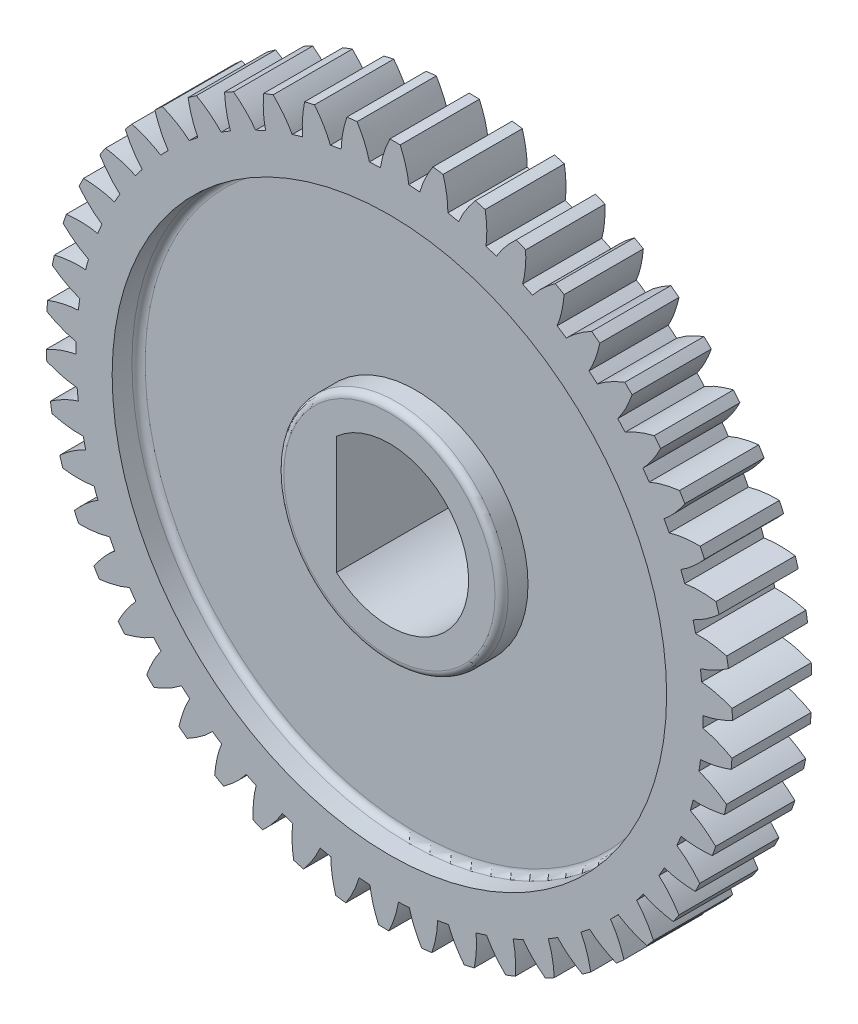
SolidWorks part; units mm, degrees
ref_plane "Plan de face" through (0, 0, 0) normal (0, 0, 1) x (1, 0, 0)
ref_plane "Plan de dessus" through (0, 0, 0) normal (0, 1, 0) x (1, 0, 0)
ref_plane "Plan de droite" through (0, 0, 0) normal (1, 0, 0) x (0, 0, -1)
sketch "Esquisse1" plane through (0, 0, 0) normal (0, 0, 1) x (1, 0, 0)
  line L0 (-2, 2.2361) -> (-2, -2.2361)
  arc A0 (12.9936, 0.4084) -> (12.9756, 0.7954) centre (0, 0) ccw
  arc A1 (12.8399, 2.0337) -> (12.7736, 2.4154) centre (0, 0) ccw
  arc A2 (12.4838, 3.6269) -> (12.3702, 3.9974) centre (0, 0) ccw
  arc A3 (11.9308, 5.1629) -> (11.7716, 5.5162) centre (0, 0) ccw
  arc A4 (11.1896, 6.6175) -> (10.9874, 6.9481) centre (0, 0) ccw
  arc A5 (10.272, 7.9678) -> (10.03, 8.2704) centre (0, 0) ccw
  arc A6 (9.1924, 9.1924) -> (8.9143, 9.4623) centre (0, 0) ccw
  arc A7 (7.9678, 10.272) -> (7.6581, 10.5049) centre (0, 0) ccw
  arc A8 (6.6175, 11.1897) -> (6.2811, 11.3819) centre (0, 0) ccw
  arc A9 (5.1629, 11.9308) -> (4.805, 12.0794) centre (0, 0) ccw
  arc A10 (3.6269, 12.4838) -> (3.2532, 12.5864) centre (0, 0) ccw
  arc A11 (2.0336, 12.84) -> (1.6501, 12.8949) centre (0, 0) ccw
  arc A12 (0.4083, 12.9936) -> (0.0209, 13) centre (0, 0) ccw
  arc A13 (-1.2234, 12.9423) -> (-1.6086, 12.9001) centre (0, 0) ccw
  arc A14 (-2.8359, 12.6869) -> (-3.2127, 12.5968) centre (0, 0) ccw
  arc A15 (-4.4036, 12.2314) -> (-4.7662, 12.0948) centre (0, 0) ccw
  arc A16 (-5.9019, 11.5831) -> (-6.2445, 11.402) centre (0, 0) ccw
  arc A17 (-7.3071, 10.752) -> (-7.6243, 10.5295) centre (0, 0) ccw
  arc A18 (-8.5971, 9.7514) -> (-8.8839, 9.4909) centre (0, 0) ccw
  arc A19 (-9.7515, 8.597) -> (-10.0033, 8.3026) centre (0, 0) ccw
  arc A20 (-10.7521, 7.3071) -> (-10.9651, 6.9834) centre (0, 0) ccw
  arc A21 (-11.5831, 5.9019) -> (-11.7538, 5.554) centre (0, 0) ccw
  arc A22 (-12.2315, 4.4036) -> (-12.3573, 4.0371) centre (0, 0) ccw
  arc A23 (-12.6869, 2.8358) -> (-12.7658, 2.4565) centre (0, 0) ccw
  arc A24 (-12.9423, 1.2234) -> (-12.973, 0.8371) centre (0, 0) ccw
  arc A25 (-12.9936, -0.4084) -> (-12.9756, -0.7954) centre (0, 0) ccw
  arc A26 (-12.8399, -2.0337) -> (-12.7736, -2.4154) centre (0, 0) ccw
  arc A27 (-12.4838, -3.6269) -> (-12.3702, -3.9974) centre (0, 0) ccw
  arc A28 (-11.9308, -5.1629) -> (-11.7716, -5.5162) centre (0, 0) ccw
  arc A29 (-11.1896, -6.6175) -> (-10.9874, -6.9481) centre (0, 0) ccw
  arc A30 (-10.272, -7.9678) -> (-10.03, -8.2704) centre (0, 0) ccw
  arc A31 (-9.1924, -9.1924) -> (-8.9143, -9.4623) centre (0, 0) ccw
  arc A32 (-7.9678, -10.272) -> (-7.6581, -10.5049) centre (0, 0) ccw
  arc A33 (-6.6175, -11.1897) -> (-6.2811, -11.3819) centre (0, 0) ccw
  arc A34 (-5.1629, -11.9308) -> (-4.805, -12.0794) centre (0, 0) ccw
  arc A35 (-3.6269, -12.4838) -> (-3.2532, -12.5864) centre (0, 0) ccw
  arc A36 (-2.0336, -12.84) -> (-1.6501, -12.8949) centre (0, 0) ccw
  arc A37 (-0.4083, -12.9936) -> (-0.0209, -13) centre (0, 0) ccw
  arc A38 (1.2234, -12.9423) -> (1.6086, -12.9001) centre (0, 0) ccw
  arc A39 (2.8359, -12.6869) -> (3.2127, -12.5968) centre (0, 0) ccw
  arc A40 (4.4036, -12.2314) -> (4.7662, -12.0948) centre (0, 0) ccw
  arc A41 (5.9019, -11.5831) -> (6.2445, -11.402) centre (0, 0) ccw
  arc A42 (7.3071, -10.752) -> (7.6243, -10.5295) centre (0, 0) ccw
  arc A43 (8.5971, -9.7514) -> (8.8839, -9.4909) centre (0, 0) ccw
  arc A44 (9.7515, -8.597) -> (10.0033, -8.3026) centre (0, 0) ccw
  arc A45 (10.7521, -7.3071) -> (10.9651, -6.9834) centre (0, 0) ccw
  arc A46 (11.5831, -5.9019) -> (11.7538, -5.554) centre (0, 0) ccw
  arc A47 (12.2315, -4.4036) -> (12.3573, -4.0371) centre (0, 0) ccw
  arc A48 (12.6869, -2.8358) -> (12.7658, -2.4565) centre (0, 0) ccw
  arc A49 (12.9423, -1.2234) -> (12.973, -0.8371) centre (0, 0) ccw
  arc A50 (11.8681, -0.4041) -> (11.875, 0.012) centre (0, 0) ccw
  arc A51 (11.8252, 1.0866) -> (11.7798, 1.5003) centre (0, 0) ccw
  arc A52 (11.5958, 2.5601) -> (11.4989, 2.9648) centre (0, 0) ccw
  arc A53 (11.1835, 3.9932) -> (11.0367, 4.3827) centre (0, 0) ccw
  arc A54 (10.5948, 5.3634) -> (10.4003, 5.7314) centre (0, 0) ccw
  arc A55 (9.839, 6.649) -> (9.6, 6.9897) centre (0, 0) ccw
  arc A56 (8.9281, 7.8297) -> (8.6483, 8.1378) centre (0, 0) ccw
  arc A57 (7.8764, 8.887) -> (7.5601, 9.1575) centre (0, 0) ccw
  arc A58 (6.7004, 9.8041) -> (6.3528, 10.0328) centre (0, 0) ccw
  arc A59 (5.4188, 10.5666) -> (5.0452, 10.7499) centre (0, 0) ccw
  arc A60 (4.0518, 11.1624) -> (3.6581, 11.2975) centre (0, 0) ccw
  arc A61 (2.6208, 11.5822) -> (2.2133, 11.6669) centre (0, 0) ccw
  arc A62 (1.1485, 11.8193) -> (0.7336, 11.8523) centre (0, 0) ccw
  arc A63 (-0.3419, 11.8701) -> (-0.7576, 11.8508) centre (0, 0) ccw
  arc A64 (-1.8269, 11.7336) -> (-2.237, 11.6624) centre (0, 0) ccw
  arc A65 (-3.2831, 11.4121) -> (-3.681, 11.2901) centre (0, 0) ccw
  arc A66 (-4.6876, 10.9106) -> (-5.067, 10.7397) centre (0, 0) ccw
  arc A67 (-6.0181, 10.2371) -> (-6.3731, 10.0199) centre (0, 0) ccw
  arc A68 (-7.2537, 9.4021) -> (-7.5787, 9.1422) centre (0, 0) ccw
  arc A69 (-8.3749, 8.4189) -> (-8.6647, 8.1202) centre (0, 0) ccw
  arc A70 (-9.364, 7.3028) -> (-9.6141, 6.9702) centre (0, 0) ccw
  arc A71 (-10.2054, 6.0716) -> (-10.4119, 5.7103) centre (0, 0) ccw
  arc A72 (-10.886, 4.7447) -> (-11.0455, 4.3603) centre (0, 0) ccw
  arc A73 (-11.3948, 3.3429) -> (-11.5049, 2.9415) centre (0, 0) ccw
  arc A74 (-11.7239, 1.8884) -> (-11.7829, 1.4764) centre (0, 0) ccw
  arc A75 (-11.8681, 0.4041) -> (-11.875, -0.012) centre (0, 0) ccw
  arc A76 (-11.8252, -1.0866) -> (-11.7798, -1.5003) centre (0, 0) ccw
  arc A77 (-11.5958, -2.5601) -> (-11.4989, -2.9648) centre (0, 0) ccw
  arc A78 (-11.1835, -3.9932) -> (-11.0367, -4.3827) centre (0, 0) ccw
  arc A79 (-10.5948, -5.3634) -> (-10.4003, -5.7314) centre (0, 0) ccw
  arc A80 (-9.839, -6.649) -> (-9.6, -6.9897) centre (0, 0) ccw
  arc A81 (-8.9281, -7.8297) -> (-8.6483, -8.1378) centre (0, 0) ccw
  arc A82 (-7.8764, -8.887) -> (-7.5601, -9.1575) centre (0, 0) ccw
  arc A83 (-6.7004, -9.8041) -> (-6.3528, -10.0328) centre (0, 0) ccw
  arc A84 (-5.4188, -10.5666) -> (-5.0452, -10.7499) centre (0, 0) ccw
  arc A85 (-4.0518, -11.1624) -> (-3.6581, -11.2975) centre (0, 0) ccw
  arc A86 (-2.6208, -11.5822) -> (-2.2133, -11.6669) centre (0, 0) ccw
  arc A87 (-1.1485, -11.8193) -> (-0.7336, -11.8523) centre (0, 0) ccw
  arc A88 (0.3419, -11.8701) -> (0.7576, -11.8508) centre (0, 0) ccw
  arc A89 (1.8269, -11.7336) -> (2.237, -11.6624) centre (0, 0) ccw
  arc A90 (3.2831, -11.4121) -> (3.681, -11.2901) centre (0, 0) ccw
  arc A91 (4.6876, -10.9106) -> (5.067, -10.7397) centre (0, 0) ccw
  arc A92 (6.0181, -10.2371) -> (6.3731, -10.0199) centre (0, 0) ccw
  arc A93 (7.2537, -9.4021) -> (7.5787, -9.1422) centre (0, 0) ccw
  arc A94 (8.3749, -8.4189) -> (8.6647, -8.1202) centre (0, 0) ccw
  arc A95 (9.364, -7.3028) -> (9.6141, -6.9702) centre (0, 0) ccw
  arc A96 (10.2054, -6.0716) -> (10.4119, -5.7103) centre (0, 0) ccw
  arc A97 (10.886, -4.7447) -> (11.0455, -4.3603) centre (0, 0) ccw
  arc A98 (11.3948, -3.3429) -> (11.5049, -2.9415) centre (0, 0) ccw
  arc A99 (11.7239, -1.8884) -> (11.7829, -1.4764) centre (0, 0) ccw
  arc A100 (-2, -2.2361) -> (-2, 2.2361) centre (0, 0) ccw
  spline S0 degree 3 poles (11.875, 0.012) (11.8924, 0.0149) (12.1056, 0.0543) (12.4729, 0.1636) (12.819, 0.3195) (12.9805, 0.4016) (12.9936, 0.4084) knots 0.129628 0.129628 0.129628 0.129628 0.182246 0.777177 1.275527 1.319645 1.319645 1.319645 1.319645
  spline S1 degree 3 poles (11.8252, 1.0866) (11.8427, 1.0853) (12.0587, 1.0658) (12.4346, 0.991) (12.7936, 0.8677) (12.962, 0.8009) (12.9756, 0.7954) knots 0.129628 0.129628 0.129628 0.129628 0.182246 0.777177 1.275527 1.319645 1.319645 1.319645 1.319645
  spline S2 degree 3 poles (11.7798, 1.5003) (11.7967, 1.5053) (12.0034, 1.5711) (12.3541, 1.7256) (12.6778, 1.9236) (12.8278, 2.0253) (12.8399, 2.0337) knots 0.129628 0.129628 0.129628 0.129628 0.182246 0.777177 1.275527 1.319645 1.319645 1.319645 1.319645
  spline S3 degree 3 poles (11.5958, 2.5601) (11.6133, 2.5611) (11.8301, 2.5688) (12.2123, 2.5416) (12.5839, 2.4644) (12.7594, 2.4192) (12.7736, 2.4154) knots 0.129628 0.129628 0.129628 0.129628 0.182246 0.777177 1.275527 1.319645 1.319645 1.319645 1.319645
  spline S4 degree 3 poles (11.4989, 2.9648) (11.515, 2.9719) (11.7118, 3.0631) (12.0404, 3.2603) (12.3368, 3.4974) (12.4728, 3.6171) (12.4838, 3.6269) knots 0.129628 0.129628 0.129628 0.129628 0.182246 0.777177 1.275527 1.319645 1.319645 1.319645 1.319645
  spline S5 degree 3 poles (11.1835, 3.9932) (11.2008, 3.9964) (11.4148, 4.0312) (11.7975, 4.0522) (12.1758, 4.0221) (12.3556, 3.9993) (12.3702, 3.9974) knots 0.129628 0.129628 0.129628 0.129628 0.182246 0.777177 1.275527 1.319645 1.319645 1.319645 1.319645
  spline S6 degree 3 poles (11.0367, 4.3827) (11.0518, 4.3917) (11.2355, 4.5069) (11.5368, 4.7437) (11.8012, 5.0161) (11.9211, 5.1519) (11.9308, 5.1629) knots 0.129628 0.129628 0.129628 0.129628 0.182246 0.777177 1.275527 1.319645 1.319645 1.319645 1.319645
  spline S7 degree 3 poles (10.5948, 5.3634) (10.6116, 5.3687) (10.8196, 5.4301) (11.1966, 5.4989) (11.5757, 5.5164) (11.7569, 5.5163) (11.7716, 5.5162) knots 0.129628 0.129628 0.129628 0.129628 0.182246 0.777177 1.275527 1.319645 1.319645 1.319645 1.319645
  spline S8 degree 3 poles (10.4003, 5.7314) (10.4142, 5.7422) (10.5821, 5.8795) (10.8513, 6.1522) (11.0794, 6.4556) (11.1814, 6.6053) (11.1896, 6.6175) knots 0.129628 0.129628 0.129628 0.129628 0.182246 0.777177 1.275527 1.319645 1.319645 1.319645 1.319645
  spline S9 degree 3 poles (9.839, 6.649) (9.855, 6.6564) (10.0537, 6.7433) (10.4191, 6.8588) (10.793, 6.9238) (10.9728, 6.9463) (10.9874, 6.9481) knots 0.129628 0.129628 0.129628 0.129628 0.182246 0.777177 1.275527 1.319645 1.319645 1.319645 1.319645
  spline S10 degree 3 poles (9.6, 6.9897) (9.6124, 7.0022) (9.7617, 7.1594) (9.9947, 7.4638) (10.183, 7.7933) (10.2654, 7.9547) (10.272, 7.9678) knots 0.129628 0.129628 0.129628 0.129628 0.182246 0.777177 1.275527 1.319645 1.319645 1.319645 1.319645
  spline S11 degree 3 poles (8.9281, 7.8297) (8.943, 7.839) (9.1293, 7.9502) (9.4773, 8.1106) (9.8402, 8.2219) (10.0157, 8.2668) (10.03, 8.2704) knots 0.129628 0.129628 0.129628 0.129628 0.182246 0.777177 1.275527 1.319645 1.319645 1.319645 1.319645
  spline S12 degree 3 poles (8.6483, 8.1378) (8.659, 8.1517) (8.7874, 8.3265) (8.9804, 8.6576) (9.1259, 9.0081) (9.1874, 9.1785) (9.1924, 9.1924) knots 0.129628 0.129628 0.129628 0.129628 0.182246 0.777177 1.275527 1.319645 1.319645 1.319645 1.319645
  spline S13 degree 3 poles (7.8764, 8.887) (7.89, 8.8981) (8.0608, 9.0317) (8.386, 9.2344) (8.7321, 9.3904) (8.9006, 9.4569) (8.9143, 9.4623) knots 0.129628 0.129628 0.129628 0.129628 0.182246 0.777177 1.275527 1.319645 1.319645 1.319645 1.319645
  spline S14 degree 3 poles (7.5601, 9.1575) (7.569, 9.1727) (7.6746, 9.3622) (7.8245, 9.7148) (7.9249, 10.0809) (7.9646, 10.2576) (7.9678, 10.272) knots 0.129628 0.129628 0.129628 0.129628 0.182246 0.777177 1.275527 1.319645 1.319645 1.319645 1.319645
  spline S15 degree 3 poles (6.7004, 9.8041) (6.7126, 9.8168) (6.8653, 9.9708) (7.1625, 10.2127) (7.4863, 10.4107) (7.6451, 10.4979) (7.6581, 10.5049) knots 0.129628 0.129628 0.129628 0.129628 0.182246 0.777177 1.275527 1.319645 1.319645 1.319645 1.319645
  spline S16 degree 3 poles (6.3528, 10.0328) (6.3597, 10.049) (6.4407, 10.2502) (6.5452, 10.6189) (6.599, 10.9946) (6.6162, 11.175) (6.6175, 11.1897) knots 0.129628 0.129628 0.129628 0.129628 0.182246 0.777177 1.275527 1.319645 1.319645 1.319645 1.319645
  spline S17 degree 3 poles (5.4188, 10.5666) (5.4293, 10.5807) (5.5615, 10.7526) (5.8261, 11.0299) (6.1225, 11.2669) (6.2691, 11.3733) (6.2811, 11.3819) knots 0.129628 0.129628 0.129628 0.129628 0.182246 0.777177 1.275527 1.319645 1.319645 1.319645 1.319645
  spline S18 degree 3 poles (5.0452, 10.7499) (5.0501, 10.7669) (5.1052, 10.9766) (5.1627, 11.3555) (5.169, 11.735) (5.1634, 11.9161) (5.1629, 11.9308) knots 0.129628 0.129628 0.129628 0.129628 0.182246 0.777177 1.275527 1.319645 1.319645 1.319645 1.319645
  spline S19 degree 3 poles (4.0518, 11.1624) (4.0604, 11.1777) (4.17, 11.3649) (4.3977, 11.6731) (4.6621, 11.9454) (4.7942, 12.0694) (4.805, 12.0794) knots 0.129628 0.129628 0.129628 0.129628 0.182246 0.777177 1.275527 1.319645 1.319645 1.319645 1.319645
  spline S20 degree 3 poles (3.6581, 11.2975) (3.6608, 11.3149) (3.6892, 11.5299) (3.6988, 11.913) (3.6574, 12.2903) (3.6292, 12.4693) (3.6269, 12.4838) knots 0.129628 0.129628 0.129628 0.129628 0.182246 0.777177 1.275527 1.319645 1.319645 1.319645 1.319645
  spline S21 degree 3 poles (2.6208, 11.5822) (2.6274, 11.5985) (2.7127, 11.7979) (2.9, 12.1322) (3.1282, 12.4355) (3.2437, 12.5751) (3.2532, 12.5864) knots 0.129628 0.129628 0.129628 0.129628 0.182246 0.777177 1.275527 1.319645 1.319645 1.319645 1.319645
  spline S22 degree 3 poles (2.2133, 11.6669) (2.2138, 11.6845) (2.215, 11.9014) (2.1765, 12.2827) (2.0882, 12.6518) (2.0378, 12.8258) (2.0336, 12.84) knots 0.129628 0.129628 0.129628 0.129628 0.182246 0.777177 1.275527 1.319645 1.319645 1.319645 1.319645
  spline S23 degree 3 poles (1.1485, 11.8193) (1.153, 11.8363) (1.2126, 12.0449) (1.3566, 12.4) (1.5449, 12.7295) (1.6421, 12.8824) (1.6501, 12.8949) knots 0.129628 0.129628 0.129628 0.129628 0.182246 0.777177 1.275527 1.319645 1.319645 1.319645 1.319645
  spline S24 degree 3 poles (0.7336, 11.8523) (0.7319, 11.8698) (0.7059, 12.0851) (0.6199, 12.4586) (0.486, 12.8137) (0.4142, 12.9801) (0.4083, 12.9936) knots 0.129628 0.129628 0.129628 0.129628 0.182246 0.777177 1.275527 1.319645 1.319645 1.319645 1.319645
  spline S25 degree 3 poles (-0.3419, 11.8701) (-0.3396, 11.8875) (-0.3065, 12.1019) (-0.2082, 12.4723) (-0.0627, 12.8228) (0.0146, 12.9867) (0.0209, 13) knots 0.129628 0.129628 0.129628 0.129628 0.182246 0.777177 1.275527 1.319645 1.319645 1.319645 1.319645
  spline S26 degree 3 poles (-0.7576, 11.8508) (-0.7616, 11.868) (-0.8143, 12.0783) (-0.9465, 12.438) (-1.1238, 12.7736) (-1.2159, 12.9296) (-1.2234, 12.9423) knots 0.129628 0.129628 0.129628 0.129628 0.182246 0.777177 1.275527 1.319645 1.319645 1.319645 1.319645
  spline S27 degree 3 poles (-1.8269, 11.7336) (-1.8268, 11.7512) (-1.8209, 11.968) (-1.7698, 12.3478) (-1.6693, 12.7138) (-1.6132, 12.8861) (-1.6086, 12.9001) knots 0.129628 0.129628 0.129628 0.129628 0.182246 0.777177 1.275527 1.319645 1.319645 1.319645 1.319645
  spline S28 degree 3 poles (-2.237, 11.6624) (-2.243, 11.6789) (-2.3217, 11.881) (-2.4979, 12.2213) (-2.7159, 12.532) (-2.8268, 12.6753) (-2.8359, 12.6869) knots 0.129628 0.129628 0.129628 0.129628 0.182246 0.777177 1.275527 1.319645 1.319645 1.319645 1.319645
  spline S29 degree 3 poles (-3.2831, 11.4121) (-3.2852, 11.4296) (-3.3065, 11.6454) (-3.3034, 12.0286) (-3.2496, 12.4044) (-3.2156, 12.5823) (-3.2127, 12.5968) knots 0.129628 0.129628 0.129628 0.129628 0.182246 0.777177 1.275527 1.319645 1.319645 1.319645 1.319645
  spline S30 degree 3 poles (-3.681, 11.2901) (-3.6891, 11.3057) (-3.7925, 11.4963) (-4.0099, 11.8119) (-4.2652, 12.0928) (-4.3932, 12.2211) (-4.4036, 12.2314) knots 0.129628 0.129628 0.129628 0.129628 0.182246 0.777177 1.275527 1.319645 1.319645 1.319645 1.319645
  spline S31 degree 3 poles (-4.6876, 10.9106) (-4.6918, 10.9277) (-4.74, 11.1392) (-4.785, 11.5198) (-4.7787, 11.8993) (-4.7672, 12.0801) (-4.7662, 12.0948) knots 0.129628 0.129628 0.129628 0.129628 0.182246 0.777177 1.275527 1.319645 1.319645 1.319645 1.319645
  spline S32 degree 3 poles (-5.067, 10.7397) (-5.077, 10.7542) (-5.2035, 10.9304) (-5.4587, 11.2162) (-5.7472, 11.4629) (-5.8902, 11.5741) (-5.9019, 11.5831) knots 0.129628 0.129628 0.129628 0.129628 0.182246 0.777177 1.275527 1.319645 1.319645 1.319645 1.319645
  spline S33 degree 3 poles (-6.0181, 10.2371) (-6.0244, 10.2535) (-6.0987, 10.4573) (-6.191, 10.8292) (-6.2324, 11.2065) (-6.2436, 11.3873) (-6.2445, 11.402) knots 0.129628 0.129628 0.129628 0.129628 0.182246 0.777177 1.275527 1.319645 1.319645 1.319645 1.319645
  spline S34 degree 3 poles (-6.3731, 10.0199) (-6.3848, 10.0331) (-6.5324, 10.192) (-6.8215, 10.4436) (-7.1385, 10.6522) (-7.2944, 10.7446) (-7.3071, 10.752) knots 0.129628 0.129628 0.129628 0.129628 0.182246 0.777177 1.275527 1.319645 1.319645 1.319645 1.319645
  spline S35 degree 3 poles (-7.2537, 9.4021) (-7.262, 9.4176) (-7.3613, 9.6104) (-7.4995, 9.9679) (-7.5878, 10.337) (-7.6216, 10.515) (-7.6243, 10.5295) knots 0.129628 0.129628 0.129628 0.129628 0.182246 0.777177 1.275527 1.319645 1.319645 1.319645 1.319645
  spline S36 degree 3 poles (-7.5787, 9.1422) (-7.5919, 9.1537) (-7.7583, 9.2929) (-8.0766, 9.5063) (-8.4173, 9.6735) (-8.5835, 9.7456) (-8.5971, 9.7514) knots 0.129628 0.129628 0.129628 0.129628 0.182246 0.777177 1.275527 1.319645 1.319645 1.319645 1.319645
  spline S37 degree 3 poles (-8.3749, 8.4189) (-8.3851, 8.4332) (-8.5077, 8.612) (-8.6897, 8.9493) (-8.8235, 9.3045) (-8.8794, 9.4768) (-8.8839, 9.4909) knots 0.129628 0.129628 0.129628 0.129628 0.182246 0.777177 1.275527 1.319645 1.319645 1.319645 1.319645
  spline S38 degree 3 poles (-8.6647, 8.1202) (-8.6793, 8.13) (-8.8618, 8.2473) (-9.2044, 8.4191) (-9.5633, 8.5423) (-9.7373, 8.593) (-9.7515, 8.597) knots 0.129628 0.129628 0.129628 0.129628 0.182246 0.777177 1.275527 1.319645 1.319645 1.319645 1.319645
  spline S39 degree 3 poles (-9.364, 7.3028) (-9.3759, 7.3157) (-9.52, 7.4778) (-9.7428, 7.7897) (-9.9201, 8.1252) (-9.9971, 8.2892) (-10.0033, 8.3026) knots 0.129628 0.129628 0.129628 0.129628 0.182246 0.777177 1.275527 1.319645 1.319645 1.319645 1.319645
  spline S40 degree 3 poles (-9.6141, 6.9702) (-9.6299, 6.9781) (-9.8256, 7.0716) (-10.187, 7.1991) (-10.5586, 7.2763) (-10.7375, 7.3048) (-10.7521, 7.3071) knots 0.129628 0.129628 0.129628 0.129628 0.182246 0.777177 1.275527 1.319645 1.319645 1.319645 1.319645
  spline S41 degree 3 poles (-10.2054, 6.0716) (-10.2189, 6.0829) (-10.3822, 6.2257) (-10.6423, 6.5071) (-10.8603, 6.8179) (-10.9572, 6.9709) (-10.9651, 6.9834) knots 0.129628 0.129628 0.129628 0.129628 0.182246 0.777177 1.275527 1.319645 1.319645 1.319645 1.319645
  spline S42 degree 3 poles (-10.4119, 5.7103) (-10.4285, 5.7161) (-10.6344, 5.7843) (-11.0089, 5.8655) (-11.3873, 5.8956) (-11.5684, 5.9014) (-11.5831, 5.9019) knots 0.129628 0.129628 0.129628 0.129628 0.182246 0.777177 1.275527 1.319645 1.319645 1.319645 1.319645
  spline S43 degree 3 poles (-10.886, 4.7447) (-10.9007, 4.7542) (-11.0806, 4.8754) (-11.3739, 5.122) (-11.6291, 5.4029) (-11.7445, 5.5426) (-11.7538, 5.554) knots 0.129628 0.129628 0.129628 0.129628 0.182246 0.777177 1.275527 1.319645 1.319645 1.319645 1.319645
  spline S44 degree 3 poles (-11.0455, 4.3603) (-11.0627, 4.364) (-11.2755, 4.4059) (-11.6573, 4.4395) (-12.0364, 4.4219) (-12.2168, 4.405) (-12.2315, 4.4036) knots 0.129628 0.129628 0.129628 0.129628 0.182246 0.777177 1.275527 1.319645 1.319645 1.319645 1.319645
  spline S45 degree 3 poles (-11.3948, 3.3429) (-11.4106, 3.3505) (-11.6043, 3.4481) (-11.9262, 3.6561) (-12.2146, 3.9028) (-12.3466, 4.0269) (-12.3573, 4.0371) knots 0.129628 0.129628 0.129628 0.129628 0.182246 0.777177 1.275527 1.319645 1.319645 1.319645 1.319645
  spline S46 degree 3 poles (-11.5049, 2.9415) (-11.5224, 2.9431) (-11.7388, 2.9579) (-12.1218, 2.9434) (-12.4957, 2.8785) (-12.6725, 2.8391) (-12.6869, 2.8358) knots 0.129628 0.129628 0.129628 0.129628 0.182246 0.777177 1.275527 1.319645 1.319645 1.319645 1.319645
  spline S47 degree 3 poles (-11.7239, 1.8884) (-11.7406, 1.8939) (-11.9449, 1.9666) (-12.2904, 2.1325) (-12.6074, 2.3412) (-12.7539, 2.4478) (-12.7658, 2.4565) knots 0.129628 0.129628 0.129628 0.129628 0.182246 0.777177 1.275527 1.319645 1.319645 1.319645 1.319645
  spline S48 degree 3 poles (-11.7829, 1.4764) (-11.8005, 1.4757) (-12.017, 1.4634) (-12.3951, 1.401) (-12.7579, 1.2897) (-12.9285, 1.2284) (-12.9423, 1.2234) knots 0.129628 0.129628 0.129628 0.129628 0.182246 0.777177 1.275527 1.319645 1.319645 1.319645 1.319645
  spline S49 degree 3 poles (-11.8681, 0.4041) (-11.8854, 0.4075) (-12.0972, 0.454) (-12.4607, 0.5753) (-12.8014, 0.7426) (-12.9601, 0.83) (-12.973, 0.8371) knots 0.129628 0.129628 0.129628 0.129628 0.182246 0.777177 1.275527 1.319645 1.319645 1.319645 1.319645
  spline S50 degree 3 poles (-11.875, -0.012) (-11.8924, -0.0149) (-12.1056, -0.0543) (-12.4729, -0.1636) (-12.819, -0.3195) (-12.9805, -0.4016) (-12.9936, -0.4084) knots 0.129628 0.129628 0.129628 0.129628 0.182246 0.777177 1.275527 1.319645 1.319645 1.319645 1.319645
  spline S51 degree 3 poles (-11.8252, -1.0866) (-11.8427, -1.0853) (-12.0587, -1.0658) (-12.4346, -0.991) (-12.7936, -0.8677) (-12.962, -0.8009) (-12.9756, -0.7954) knots 0.129628 0.129628 0.129628 0.129628 0.182246 0.777177 1.275527 1.319645 1.319645 1.319645 1.319645
  spline S52 degree 3 poles (-11.7798, -1.5003) (-11.7967, -1.5053) (-12.0034, -1.5711) (-12.3541, -1.7256) (-12.6778, -1.9236) (-12.8278, -2.0253) (-12.8399, -2.0337) knots 0.129628 0.129628 0.129628 0.129628 0.182246 0.777177 1.275527 1.319645 1.319645 1.319645 1.319645
  spline S53 degree 3 poles (-11.5958, -2.5601) (-11.6133, -2.5611) (-11.8301, -2.5688) (-12.2123, -2.5416) (-12.5839, -2.4644) (-12.7594, -2.4192) (-12.7736, -2.4154) knots 0.129628 0.129628 0.129628 0.129628 0.182246 0.777177 1.275527 1.319645 1.319645 1.319645 1.319645
  spline S54 degree 3 poles (-11.4989, -2.9648) (-11.515, -2.9719) (-11.7118, -3.0631) (-12.0404, -3.2603) (-12.3368, -3.4974) (-12.4728, -3.6171) (-12.4838, -3.6269) knots 0.129628 0.129628 0.129628 0.129628 0.182246 0.777177 1.275527 1.319645 1.319645 1.319645 1.319645
  spline S55 degree 3 poles (-11.1835, -3.9932) (-11.2008, -3.9964) (-11.4148, -4.0312) (-11.7975, -4.0522) (-12.1758, -4.0221) (-12.3556, -3.9993) (-12.3702, -3.9974) knots 0.129628 0.129628 0.129628 0.129628 0.182246 0.777177 1.275527 1.319645 1.319645 1.319645 1.319645
  spline S56 degree 3 poles (-11.0367, -4.3827) (-11.0518, -4.3917) (-11.2355, -4.5069) (-11.5368, -4.7437) (-11.8012, -5.0161) (-11.9211, -5.1519) (-11.9308, -5.1629) knots 0.129628 0.129628 0.129628 0.129628 0.182246 0.777177 1.275527 1.319645 1.319645 1.319645 1.319645
  spline S57 degree 3 poles (-10.5948, -5.3634) (-10.6116, -5.3687) (-10.8196, -5.4301) (-11.1966, -5.4989) (-11.5757, -5.5164) (-11.7569, -5.5163) (-11.7716, -5.5162) knots 0.129628 0.129628 0.129628 0.129628 0.182246 0.777177 1.275527 1.319645 1.319645 1.319645 1.319645
  spline S58 degree 3 poles (-10.4003, -5.7314) (-10.4142, -5.7422) (-10.5821, -5.8795) (-10.8513, -6.1522) (-11.0794, -6.4556) (-11.1814, -6.6053) (-11.1896, -6.6175) knots 0.129628 0.129628 0.129628 0.129628 0.182246 0.777177 1.275527 1.319645 1.319645 1.319645 1.319645
  spline S59 degree 3 poles (-9.839, -6.649) (-9.855, -6.6564) (-10.0537, -6.7433) (-10.4191, -6.8588) (-10.793, -6.9238) (-10.9728, -6.9463) (-10.9874, -6.9481) knots 0.129628 0.129628 0.129628 0.129628 0.182246 0.777177 1.275527 1.319645 1.319645 1.319645 1.319645
  spline S60 degree 3 poles (-9.6, -6.9897) (-9.6124, -7.0022) (-9.7617, -7.1594) (-9.9947, -7.4638) (-10.183, -7.7933) (-10.2654, -7.9547) (-10.272, -7.9678) knots 0.129628 0.129628 0.129628 0.129628 0.182246 0.777177 1.275527 1.319645 1.319645 1.319645 1.319645
  spline S61 degree 3 poles (-8.9281, -7.8297) (-8.943, -7.839) (-9.1293, -7.9502) (-9.4773, -8.1106) (-9.8402, -8.2219) (-10.0157, -8.2668) (-10.03, -8.2704) knots 0.129628 0.129628 0.129628 0.129628 0.182246 0.777177 1.275527 1.319645 1.319645 1.319645 1.319645
  spline S62 degree 3 poles (-8.6483, -8.1378) (-8.659, -8.1517) (-8.7874, -8.3265) (-8.9804, -8.6576) (-9.1259, -9.0081) (-9.1874, -9.1785) (-9.1924, -9.1924) knots 0.129628 0.129628 0.129628 0.129628 0.182246 0.777177 1.275527 1.319645 1.319645 1.319645 1.319645
  spline S63 degree 3 poles (-7.8764, -8.887) (-7.89, -8.8981) (-8.0608, -9.0317) (-8.386, -9.2344) (-8.7321, -9.3904) (-8.9006, -9.4569) (-8.9143, -9.4623) knots 0.129628 0.129628 0.129628 0.129628 0.182246 0.777177 1.275527 1.319645 1.319645 1.319645 1.319645
  spline S64 degree 3 poles (-7.5601, -9.1575) (-7.569, -9.1727) (-7.6746, -9.3622) (-7.8245, -9.7148) (-7.9249, -10.0809) (-7.9646, -10.2576) (-7.9678, -10.272) knots 0.129628 0.129628 0.129628 0.129628 0.182246 0.777177 1.275527 1.319645 1.319645 1.319645 1.319645
  spline S65 degree 3 poles (-6.7004, -9.8041) (-6.7126, -9.8168) (-6.8653, -9.9708) (-7.1625, -10.2127) (-7.4863, -10.4107) (-7.6451, -10.4979) (-7.6581, -10.5049) knots 0.129628 0.129628 0.129628 0.129628 0.182246 0.777177 1.275527 1.319645 1.319645 1.319645 1.319645
  spline S66 degree 3 poles (-6.3528, -10.0328) (-6.3597, -10.049) (-6.4407, -10.2502) (-6.5452, -10.6189) (-6.599, -10.9946) (-6.6162, -11.175) (-6.6175, -11.1897) knots 0.129628 0.129628 0.129628 0.129628 0.182246 0.777177 1.275527 1.319645 1.319645 1.319645 1.319645
  spline S67 degree 3 poles (-5.4188, -10.5666) (-5.4293, -10.5807) (-5.5615, -10.7526) (-5.8261, -11.0299) (-6.1225, -11.2669) (-6.2691, -11.3733) (-6.2811, -11.3819) knots 0.129628 0.129628 0.129628 0.129628 0.182246 0.777177 1.275527 1.319645 1.319645 1.319645 1.319645
  spline S68 degree 3 poles (-5.0452, -10.7499) (-5.0501, -10.7669) (-5.1052, -10.9766) (-5.1627, -11.3555) (-5.169, -11.735) (-5.1634, -11.9161) (-5.1629, -11.9308) knots 0.129628 0.129628 0.129628 0.129628 0.182246 0.777177 1.275527 1.319645 1.319645 1.319645 1.319645
  spline S69 degree 3 poles (-4.0518, -11.1624) (-4.0604, -11.1777) (-4.17, -11.3649) (-4.3977, -11.6731) (-4.6621, -11.9454) (-4.7942, -12.0694) (-4.805, -12.0794) knots 0.129628 0.129628 0.129628 0.129628 0.182246 0.777177 1.275527 1.319645 1.319645 1.319645 1.319645
  spline S70 degree 3 poles (-3.6581, -11.2975) (-3.6608, -11.3149) (-3.6892, -11.5299) (-3.6988, -11.913) (-3.6574, -12.2903) (-3.6292, -12.4693) (-3.6269, -12.4838) knots 0.129628 0.129628 0.129628 0.129628 0.182246 0.777177 1.275527 1.319645 1.319645 1.319645 1.319645
  spline S71 degree 3 poles (-2.6208, -11.5822) (-2.6274, -11.5985) (-2.7127, -11.7979) (-2.9, -12.1322) (-3.1282, -12.4355) (-3.2437, -12.5751) (-3.2532, -12.5864) knots 0.129628 0.129628 0.129628 0.129628 0.182246 0.777177 1.275527 1.319645 1.319645 1.319645 1.319645
  spline S72 degree 3 poles (-2.2133, -11.6669) (-2.2138, -11.6845) (-2.215, -11.9014) (-2.1765, -12.2827) (-2.0882, -12.6518) (-2.0378, -12.8258) (-2.0336, -12.84) knots 0.129628 0.129628 0.129628 0.129628 0.182246 0.777177 1.275527 1.319645 1.319645 1.319645 1.319645
  spline S73 degree 3 poles (-1.1485, -11.8193) (-1.153, -11.8363) (-1.2126, -12.0449) (-1.3566, -12.4) (-1.5449, -12.7295) (-1.6421, -12.8824) (-1.6501, -12.8949) knots 0.129628 0.129628 0.129628 0.129628 0.182246 0.777177 1.275527 1.319645 1.319645 1.319645 1.319645
  spline S74 degree 3 poles (-0.7336, -11.8523) (-0.7319, -11.8698) (-0.7059, -12.0851) (-0.6199, -12.4586) (-0.486, -12.8137) (-0.4142, -12.9801) (-0.4083, -12.9936) knots 0.129628 0.129628 0.129628 0.129628 0.182246 0.777177 1.275527 1.319645 1.319645 1.319645 1.319645
  spline S75 degree 3 poles (0.3419, -11.8701) (0.3396, -11.8875) (0.3065, -12.1019) (0.2082, -12.4723) (0.0627, -12.8228) (-0.0146, -12.9867) (-0.0209, -13) knots 0.129628 0.129628 0.129628 0.129628 0.182246 0.777177 1.275527 1.319645 1.319645 1.319645 1.319645
  spline S76 degree 3 poles (0.7576, -11.8508) (0.7616, -11.868) (0.8143, -12.0783) (0.9465, -12.438) (1.1238, -12.7736) (1.2159, -12.9296) (1.2234, -12.9423) knots 0.129628 0.129628 0.129628 0.129628 0.182246 0.777177 1.275527 1.319645 1.319645 1.319645 1.319645
  spline S77 degree 3 poles (1.8269, -11.7336) (1.8268, -11.7512) (1.8209, -11.968) (1.7698, -12.3478) (1.6693, -12.7138) (1.6132, -12.8861) (1.6086, -12.9001) knots 0.129628 0.129628 0.129628 0.129628 0.182246 0.777177 1.275527 1.319645 1.319645 1.319645 1.319645
  spline S78 degree 3 poles (2.237, -11.6624) (2.243, -11.6789) (2.3217, -11.881) (2.4979, -12.2213) (2.7159, -12.532) (2.8268, -12.6753) (2.8359, -12.6869) knots 0.129628 0.129628 0.129628 0.129628 0.182246 0.777177 1.275527 1.319645 1.319645 1.319645 1.319645
  spline S79 degree 3 poles (3.2831, -11.4121) (3.2852, -11.4296) (3.3065, -11.6454) (3.3034, -12.0286) (3.2496, -12.4044) (3.2156, -12.5823) (3.2127, -12.5968) knots 0.129628 0.129628 0.129628 0.129628 0.182246 0.777177 1.275527 1.319645 1.319645 1.319645 1.319645
  spline S80 degree 3 poles (3.681, -11.2901) (3.6891, -11.3057) (3.7925, -11.4963) (4.0099, -11.8119) (4.2652, -12.0928) (4.3932, -12.2211) (4.4036, -12.2314) knots 0.129628 0.129628 0.129628 0.129628 0.182246 0.777177 1.275527 1.319645 1.319645 1.319645 1.319645
  spline S81 degree 3 poles (4.6876, -10.9106) (4.6918, -10.9277) (4.74, -11.1392) (4.785, -11.5198) (4.7787, -11.8993) (4.7672, -12.0801) (4.7662, -12.0948) knots 0.129628 0.129628 0.129628 0.129628 0.182246 0.777177 1.275527 1.319645 1.319645 1.319645 1.319645
  spline S82 degree 3 poles (5.067, -10.7397) (5.077, -10.7542) (5.2035, -10.9304) (5.4587, -11.2162) (5.7472, -11.4629) (5.8902, -11.5741) (5.9019, -11.5831) knots 0.129628 0.129628 0.129628 0.129628 0.182246 0.777177 1.275527 1.319645 1.319645 1.319645 1.319645
  spline S83 degree 3 poles (6.0181, -10.2371) (6.0244, -10.2535) (6.0987, -10.4573) (6.191, -10.8292) (6.2324, -11.2065) (6.2436, -11.3873) (6.2445, -11.402) knots 0.129628 0.129628 0.129628 0.129628 0.182246 0.777177 1.275527 1.319645 1.319645 1.319645 1.319645
  spline S84 degree 3 poles (6.3731, -10.0199) (6.3848, -10.0331) (6.5324, -10.192) (6.8215, -10.4436) (7.1385, -10.6522) (7.2944, -10.7446) (7.3071, -10.752) knots 0.129628 0.129628 0.129628 0.129628 0.182246 0.777177 1.275527 1.319645 1.319645 1.319645 1.319645
  spline S85 degree 3 poles (7.2537, -9.4021) (7.262, -9.4176) (7.3613, -9.6104) (7.4995, -9.9679) (7.5878, -10.337) (7.6216, -10.515) (7.6243, -10.5295) knots 0.129628 0.129628 0.129628 0.129628 0.182246 0.777177 1.275527 1.319645 1.319645 1.319645 1.319645
  spline S86 degree 3 poles (7.5787, -9.1422) (7.5919, -9.1537) (7.7583, -9.2929) (8.0766, -9.5063) (8.4173, -9.6735) (8.5835, -9.7456) (8.5971, -9.7514) knots 0.129628 0.129628 0.129628 0.129628 0.182246 0.777177 1.275527 1.319645 1.319645 1.319645 1.319645
  spline S87 degree 3 poles (8.3749, -8.4189) (8.3851, -8.4332) (8.5077, -8.612) (8.6897, -8.9493) (8.8235, -9.3045) (8.8794, -9.4768) (8.8839, -9.4909) knots 0.129628 0.129628 0.129628 0.129628 0.182246 0.777177 1.275527 1.319645 1.319645 1.319645 1.319645
  spline S88 degree 3 poles (8.6647, -8.1202) (8.6793, -8.13) (8.8618, -8.2473) (9.2044, -8.4191) (9.5633, -8.5423) (9.7373, -8.593) (9.7515, -8.597) knots 0.129628 0.129628 0.129628 0.129628 0.182246 0.777177 1.275527 1.319645 1.319645 1.319645 1.319645
  spline S89 degree 3 poles (9.364, -7.3028) (9.3759, -7.3157) (9.52, -7.4778) (9.7428, -7.7897) (9.9201, -8.1252) (9.9971, -8.2892) (10.0033, -8.3026) knots 0.129628 0.129628 0.129628 0.129628 0.182246 0.777177 1.275527 1.319645 1.319645 1.319645 1.319645
  spline S90 degree 3 poles (9.6141, -6.9702) (9.6299, -6.9781) (9.8256, -7.0716) (10.187, -7.1991) (10.5586, -7.2763) (10.7375, -7.3048) (10.7521, -7.3071) knots 0.129628 0.129628 0.129628 0.129628 0.182246 0.777177 1.275527 1.319645 1.319645 1.319645 1.319645
  spline S91 degree 3 poles (10.2054, -6.0716) (10.2189, -6.0829) (10.3822, -6.2257) (10.6423, -6.5071) (10.8603, -6.8179) (10.9572, -6.9709) (10.9651, -6.9834) knots 0.129628 0.129628 0.129628 0.129628 0.182246 0.777177 1.275527 1.319645 1.319645 1.319645 1.319645
  spline S92 degree 3 poles (10.4119, -5.7103) (10.4285, -5.7161) (10.6344, -5.7843) (11.0089, -5.8655) (11.3873, -5.8956) (11.5684, -5.9014) (11.5831, -5.9019) knots 0.129628 0.129628 0.129628 0.129628 0.182246 0.777177 1.275527 1.319645 1.319645 1.319645 1.319645
  spline S93 degree 3 poles (10.886, -4.7447) (10.9007, -4.7542) (11.0806, -4.8754) (11.3739, -5.122) (11.6291, -5.4029) (11.7445, -5.5426) (11.7538, -5.554) knots 0.129628 0.129628 0.129628 0.129628 0.182246 0.777177 1.275527 1.319645 1.319645 1.319645 1.319645
  spline S94 degree 3 poles (11.0455, -4.3603) (11.0627, -4.364) (11.2755, -4.4059) (11.6573, -4.4395) (12.0364, -4.4219) (12.2168, -4.405) (12.2315, -4.4036) knots 0.129628 0.129628 0.129628 0.129628 0.182246 0.777177 1.275527 1.319645 1.319645 1.319645 1.319645
  spline S95 degree 3 poles (11.3948, -3.3429) (11.4106, -3.3505) (11.6043, -3.4481) (11.9262, -3.6561) (12.2146, -3.9028) (12.3466, -4.0269) (12.3573, -4.0371) knots 0.129628 0.129628 0.129628 0.129628 0.182246 0.777177 1.275527 1.319645 1.319645 1.319645 1.319645
  spline S96 degree 3 poles (11.5049, -2.9415) (11.5224, -2.9431) (11.7388, -2.9579) (12.1218, -2.9434) (12.4957, -2.8785) (12.6725, -2.8391) (12.6869, -2.8358) knots 0.129628 0.129628 0.129628 0.129628 0.182246 0.777177 1.275527 1.319645 1.319645 1.319645 1.319645
  spline S97 degree 3 poles (11.7239, -1.8884) (11.7406, -1.8939) (11.9449, -1.9666) (12.2904, -2.1325) (12.6074, -2.3412) (12.7539, -2.4478) (12.7658, -2.4565) knots 0.129628 0.129628 0.129628 0.129628 0.182246 0.777177 1.275527 1.319645 1.319645 1.319645 1.319645
  spline S98 degree 3 poles (11.7829, -1.4764) (11.8005, -1.4757) (12.017, -1.4634) (12.3951, -1.401) (12.7579, -1.2897) (12.9285, -1.2284) (12.9423, -1.2234) knots 0.129628 0.129628 0.129628 0.129628 0.182246 0.777177 1.275527 1.319645 1.319645 1.319645 1.319645
  spline S99 degree 3 poles (11.8681, -0.4041) (11.8854, -0.4075) (12.0972, -0.454) (12.4607, -0.5753) (12.8014, -0.7426) (12.9601, -0.83) (12.973, -0.8371) knots 0.129628 0.129628 0.129628 0.129628 0.182246 0.777177 1.275527 1.319645 1.319645 1.319645 1.319645
  dimension "D1" = 6
  dimension "D2" = 2
extrude "Boss.-Extru.1" add sketch "Esquisse1" along normal blind 3
sketch "Esquisse2" plane through (0, 0, 3) normal (0, 0, 1) x (1, 0, 0)
  circle A0 centre (0, 0) radius 4.25
  circle A1 centre (0, 0) radius 10.5
  dimension "D1" = 21
  dimension "D2" = 8.5
extrude "Enlèv. mat.-Extru.1" cut sketch "Esquisse2" against normal blind 1
sketch "Esquisse3" plane through (0, 0, 0) normal (0, 0, -1) x (-1, 0, 0)
  line L0 (2, 2.2361) -> (2, -2.2361) construction
  line L1 (2, 2.2361) -> (2, -2.2361)
  circle A0 centre (0, 0) radius 4.25 construction
  arc A1 (2, 2.2361) -> (2, -2.2361) centre (0, 0) ccw construction
  circle A2 centre (0, 0) radius 4.25
  arc A3 (2, 2.2361) -> (2, -2.2361) centre (0, 0) ccw
extrude "Boss.-Extru.2" add sketch "Esquisse3" along normal blind 3.3
sketch "Esquisse4" plane through (0, 0, 0) normal (0, 0, -1) x (-1, 0, 0)
  line L0 (0, 0) -> (0, 14.8413) construction
  line L1 (0, 0) -> (4.6234, 17.2546) construction
  line L4 (2.01, 7.5015) -> (2.5235, 9.4178)
  line L5 (-2.01, 7.5015) -> (-2.5235, 9.4178)
  arc A0 (2.01, 7.5015) -> (-2.01, 7.5015) centre (0, 0) ccw
  arc A1 (2.5235, 9.4178) -> (-2.5235, 9.4178) centre (0, 0) ccw
  dimension "D4" = 9.75
  dimension "D2" = 7.7661
  dimension "D1" = 15
extrude "Boss.-Extru.3" add sketch "Esquisse4" along normal blind 1.75
fillet "Congé1" radius 0.25 15 edges at (4.25, 0, 3) (10.5, 0, 2) (-4.25, 0, -3.3) (2.2668, 8.4596, -1.75) (2.2668, 8.4596, 0) (0, 9.75, -1.75) (2.5235, 9.4178, -0.875) (0, 9.75, 0) (-2.2668, 8.4596, -1.75) (-2.5235, 9.4178, -0.875) (-2.2668, 8.4596, 0) (2.01, 7.5015, -0.875) (0, 7.7661, -1.75) (-2.01, 7.5015, -0.875) (0, 7.7661, 0)
